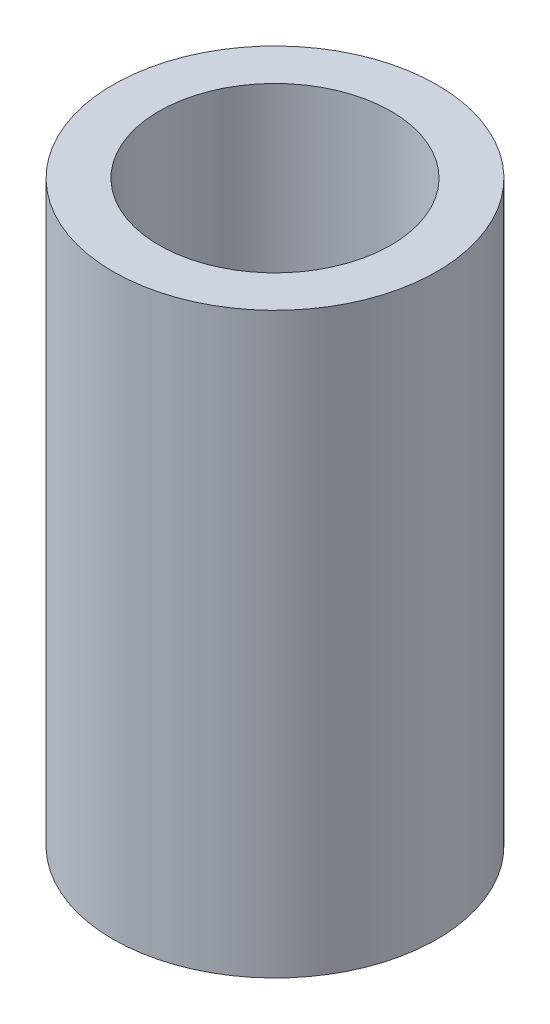
SolidWorks part; units mm, degrees
ref_plane "Front Plane" through (0, 0, 0) normal (0, 0, 1) x (1, 0, 0)
ref_plane "Top Plane" through (0, 0, 0) normal (0, 1, 0) x (1, 0, 0)
ref_plane "Right Plane" through (0, 0, 0) normal (1, 0, 0) x (0, 0, -1)
sketch "Sketch1" plane through (0, 0, 0) normal (0, 1, 0) x (1, 0, 0)
  circle A0 centre (0, 0) radius 7.6454
  circle A1 centre (0, 0) radius 10.668
  dimension "D1" = 21.336
  dimension "D2" = 15.2908
extrude "Boss-Extrude1" add sketch "Sketch1" along normal blind 38.1
